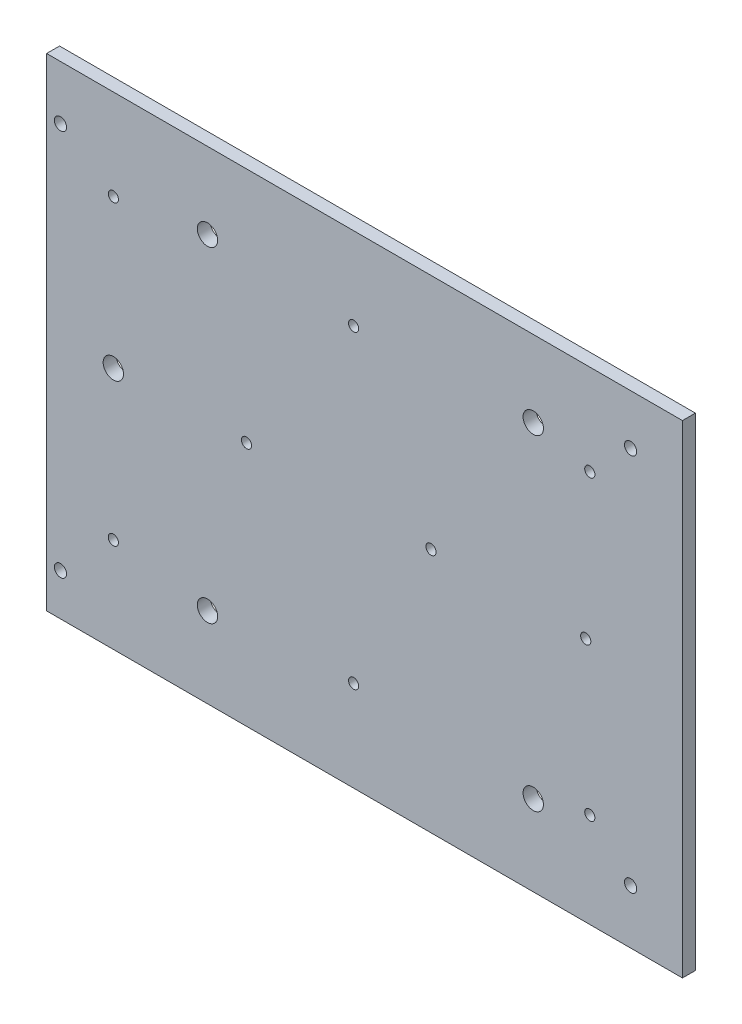
SolidWorks part; units mm, degrees
material "1060 Alloy"
ref_plane "Front Plane" through (0, 0, 0) normal (0, 0, 1) x (1, 0, 0)
ref_plane "Top Plane" through (0, 0, 0) normal (0, 1, 0) x (1, 0, 0)
ref_plane "Right Plane" through (0, 0, 0) normal (1, 0, 0) x (0, 0, -1)
sketch "Model" plane through (0, 0, 0) normal (0, 0, 1) x (1, 0, 0)
  line L0 (195.596, -46.5436) -> (195.6242, -46.5842)
  line L1 (195.6242, -46.5842) -> (195.667, -46.6123)
  line L2 (195.667, -46.6123) -> (195.7131, -46.6199)
  line L3 (195.7131, -46.6199) -> (223.0861, -46.6199)
  line L4 (223.0861, -46.6199) -> (223.0861, -165.0659)
  line L5 (223.0861, -165.0659) -> (66.9527, -165.0659)
  line L6 (66.9527, -165.0659) -> (66.9527, -46.5208)
  line L7 (66.9527, -46.5208) -> (195.5915, -46.5208)
  line L8 (195.5915, -46.5208) -> (195.596, -46.5436)
  spline S0 degree 3 poles (109.2626, -145.1929) (109.2626, -146.5998) (108.1198, -147.7426) (106.7129, -147.7426) (105.3062, -147.7426) (104.1635, -146.5998) (104.1635, -145.1929) knots 2 2 2 2 3 3 3 4 4 4 4
  spline S1 degree 3 poles (104.1635, -145.1929) (104.1635, -143.7862) (105.3062, -142.6435) (106.7129, -142.6435) (108.1198, -142.6435) (109.2626, -143.7862) (109.2626, -145.1929) knots 0 0 0 0 1 1 1 2 2 2 2
  spline S2 degree 3 poles (189.2129, -145.1929) (189.2129, -146.5723) (188.0926, -147.6933) (186.7132, -147.6933) (185.3334, -147.6933) (184.213, -146.5723) (184.213, -145.1929) knots 2 2 2 2 3 3 3 4 4 4 4
  spline S3 degree 3 poles (184.213, -145.1929) (184.213, -143.8134) (185.3334, -142.6931) (186.7132, -142.6931) (188.0926, -142.6931) (189.2129, -143.8134) (189.2129, -145.1929) knots 0 0 0 0 1 1 1 2 2 2 2
  spline S4 degree 3 poles (189.2129, -65.1924) (189.2129, -66.5716) (188.0926, -67.6942) (186.7132, -67.6942) (185.3334, -67.6942) (184.213, -66.5716) (184.213, -65.1924) knots 2 2 2 2 3 3 3 4 4 4 4
  spline S5 degree 3 poles (184.213, -65.1924) (184.213, -63.8132) (185.3334, -62.693) (186.7132, -62.693) (188.0926, -62.693) (189.2129, -63.8132) (189.2129, -65.1924) knots 0 0 0 0 1 1 1 2 2 2 2
  spline S6 degree 3 poles (109.213, -65.1924) (109.213, -66.5716) (108.0926, -67.6942) (106.7129, -67.6942) (105.3334, -67.6942) (104.2131, -66.5716) (104.2131, -65.1924) knots 2 2 2 2 3 3 3 4 4 4 4
  spline S7 degree 3 poles (104.2131, -65.1924) (104.2131, -63.8132) (105.3334, -62.693) (106.7129, -62.693) (108.0926, -62.693) (109.213, -63.8132) (109.213, -65.1924) knots 0 0 0 0 1 1 1 2 2 2 2
  spline S8 degree 3 poles (211.7669, -151.793) (211.7669, -152.6339) (211.0838, -153.3171) (210.2432, -153.3171) (209.4022, -153.3171) (208.719, -152.6339) (208.719, -151.793) knots 2 2 2 2 3 3 3 4 4 4 4
  spline S9 degree 3 poles (208.719, -151.793) (208.719, -150.9524) (209.4022, -150.2689) (210.2432, -150.2689) (211.0838, -150.2689) (211.7669, -150.9524) (211.7669, -151.793) knots 0 0 0 0 1 1 1 2 2 2 2
  spline S10 degree 3 poles (92.8348, -140.3787) (92.8348, -141.2195) (92.1517, -141.9028) (91.3111, -141.9028) (90.4701, -141.9028) (89.787, -141.2195) (89.787, -140.3787) knots 2 2 2 2 3 3 3 4 4 4 4
  spline S11 degree 3 poles (89.787, -140.3787) (89.787, -139.5355) (90.4701, -138.8548) (91.3111, -138.8548) (92.1517, -138.8548) (92.8348, -139.5355) (92.8348, -140.3787) knots 0 0 0 0 1 1 1 2 2 2 2
  spline S12 degree 3 poles (71.7672, -59.7924) (71.7672, -60.633) (71.084, -61.3163) (69.4021, -61.3163) (68.7193, -60.633) (68.7193, -59.7924) knots 2 2 2 2 3 3 4 4 4 4
  spline S13 degree 3 poles (68.7193, -59.7924) (68.7193, -58.9516) (69.4021, -58.2683) (71.084, -58.2683) (71.7672, -58.9516) (71.7672, -59.7924) knots 0 0 0 0 1 1 2 2 2 2
  spline S14 degree 3 poles (71.7672, -154.793) (71.7672, -155.6339) (71.084, -156.3171) (69.4021, -156.3171) (68.7193, -155.6339) (68.7193, -154.793) knots 2 2 2 2 3 3 4 4 4 4
  spline S15 degree 3 poles (68.7193, -154.793) (68.7193, -153.9524) (69.4021, -153.2689) (71.084, -153.2689) (71.7672, -153.9524) (71.7672, -154.793) knots 0 0 0 0 1 1 2 2 2 2
  spline S16 degree 3 poles (117.2132, -104.7934) (117.2132, -105.4945) (116.644, -106.0635) (115.943, -106.0635) (115.2422, -106.0635) (114.6731, -105.4945) (114.6731, -104.7934) knots 2 2 2 2 3 3 3 4 4 4 4
  spline S17 degree 3 poles (114.6731, -104.7934) (114.6731, -104.0925) (115.2422, -103.5234) (115.943, -103.5234) (116.644, -103.5234) (117.2132, -104.0925) (117.2132, -104.7934) knots 0 0 0 0 1 1 1 2 2 2 2
  spline S18 degree 3 poles (162.5131, -104.7934) (162.5131, -105.4945) (161.9436, -106.0635) (160.5421, -106.0635) (159.973, -105.4945) (159.973, -104.7934) knots 2 2 2 2 3 3 4 4 4 4
  spline S19 degree 3 poles (159.973, -104.7934) (159.973, -104.0925) (160.5421, -103.5234) (161.9436, -103.5234) (162.5131, -104.0925) (162.5131, -104.7934) knots 0 0 0 0 1 1 2 2 2 2
  spline S20 degree 3 poles (143.513, -66.7925) (143.513, -67.4936) (142.9439, -68.0625) (142.2428, -68.0625) (141.5421, -68.0625) (140.973, -67.4936) (140.973, -66.7925) knots 2 2 2 2 3 3 3 4 4 4 4
  spline S21 degree 3 poles (140.973, -66.7925) (140.973, -66.0916) (141.5421, -65.5226) (142.2428, -65.5226) (142.9439, -65.5226) (143.513, -66.0916) (143.513, -66.7925) knots 0 0 0 0 1 1 1 2 2 2 2
  spline S22 degree 3 poles (143.513, -142.793) (143.513, -143.4937) (142.9439, -144.0629) (142.2428, -144.0629) (141.5421, -144.0629) (140.973, -143.4937) (140.973, -142.793) knots 2 2 2 2 3 3 3 4 4 4 4
  spline S23 degree 3 poles (140.973, -142.793) (140.973, -142.0923) (141.5421, -141.5231) (142.2428, -141.5231) (142.9439, -141.5231) (143.513, -142.0923) (143.513, -142.793) knots 0 0 0 0 1 1 1 2 2 2 2
  spline S24 degree 3 poles (201.5129, -141.7929) (201.5129, -142.4936) (200.9438, -143.0631) (199.5423, -143.0631) (198.9732, -142.4936) (198.9732, -141.7929) knots 2 2 2 2 3 3 4 4 4 4
  spline S25 degree 3 poles (198.9732, -141.7929) (198.9732, -141.0922) (199.5423, -140.5227) (200.9438, -140.5227) (201.5129, -141.0922) (201.5129, -141.7929) knots 0 0 0 0 1 1 2 2 2 2
  spline S26 degree 3 poles (200.4033, -104.5826) (200.4033, -105.2837) (199.8338, -105.8526) (198.4323, -105.8526) (197.8632, -105.2837) (197.8632, -104.5826) knots 2 2 2 2 3 3 4 4 4 4
  spline S27 degree 3 poles (197.8632, -104.5826) (197.8632, -103.8817) (198.4323, -103.3127) (199.8338, -103.3127) (200.4033, -103.8817) (200.4033, -104.5826) knots 0 0 0 0 1 1 2 2 2 2
  spline S28 degree 3 poles (201.5129, -68.7941) (201.5129, -69.4926) (200.9438, -70.0641) (199.5423, -70.0641) (198.9732, -69.4926) (198.9732, -68.7941) knots 2 2 2 2 3 3 4 4 4 4
  spline S29 degree 3 poles (198.9732, -68.7941) (198.9732, -68.093) (199.5423, -67.524) (200.9438, -67.524) (201.5129, -68.093) (201.5129, -68.7941) knots 0 0 0 0 1 1 2 2 2 2
  spline S30 degree 3 poles (85.7429, -105.2938) (85.7429, -106.6731) (84.6226, -107.7932) (81.8637, -107.7932) (80.743, -106.6731) (80.743, -105.2938) knots 2 2 2 2 3 3 4 4 4 4
  spline S31 degree 3 poles (80.743, -105.2938) (80.743, -103.9146) (81.8637, -102.792) (84.6226, -102.792) (85.7429, -103.9146) (85.7429, -105.2938) knots 0 0 0 0 1 1 2 2 2 2
  spline S32 degree 3 poles (84.513, -141.7929) (84.513, -142.4936) (83.9439, -143.0631) (82.5424, -143.0631) (81.9733, -142.4936) (81.9733, -141.7929) knots 2 2 2 2 3 3 4 4 4 4
  spline S33 degree 3 poles (81.9733, -141.7929) (81.9733, -141.0922) (82.5424, -140.5227) (83.9439, -140.5227) (84.513, -141.0922) (84.513, -141.7929) knots 0 0 0 0 1 1 2 2 2 2
  spline S34 degree 3 poles (84.513, -68.7941) (84.513, -69.4926) (83.9439, -70.0641) (82.5424, -70.0641) (81.9733, -69.4926) (81.9733, -68.7941) knots 2 2 2 2 3 3 4 4 4 4
  spline S35 degree 3 poles (81.9733, -68.7941) (81.9733, -68.093) (82.5424, -67.524) (83.9439, -67.524) (84.513, -68.093) (84.513, -68.7941) knots 0 0 0 0 1 1 2 2 2 2
sketch "Sketch10" plane through (0, 0, 0) normal (0, 0, 1) x (1, 0, 0)
  line L1 (66.9527, -46.5208) -> (223.0861, -46.5208)
  line L2 (66.9527, -46.5208) -> (66.9527, -165.0659)
  line L3 (66.9527, -165.0659) -> (223.0861, -165.0659)
  line L4 (223.0861, -46.5208) -> (223.0861, -165.0659)
extrude "Boss-Extrude2" add sketch "Sketch10" along normal blind 3.175
sketch "Sketch11" plane through (0, 0, 3.175) normal (0, 0, 1) x (1, 0, 0)
  line L0 (66.9527, -46.5208) -> (195.5915, -46.5208) construction
  line L1 (106.4527, -65.2708) -> (186.4527, -65.2708) construction
  line L2 (106.4527, -65.2708) -> (106.4527, -145.2708) construction
  line L3 (106.4527, -145.2708) -> (186.4527, -145.2708) construction
  line L4 (186.4527, -65.2708) -> (186.4527, -145.2708) construction
  line L5 (66.9527, -165.0659) -> (66.9527, -46.5208) construction
  dimension "D1" = 80
  dimension "D2" = 80
  dimension "D3" = 18.75
  dimension "D4" = 39.5
hole_wizard "Ø5.0mm Dowel Hole1" positions "Sketch12" profile "Sketch13" hole size "Ø5.0" standard "ISO" end condition through all
sketch "Sketch12" plane through (0, 0, 3.175) normal (0, 0, 1) x (1, 0, 0)
  point P0 (106.4527, -65.2708)
  point P3 (186.4527, -65.2708)
  point P6 (186.4527, -145.2708)
  point P9 (106.4527, -145.2708)
sketch "Sketch13" plane through (106.4527, -65.2708, 3.175) normal (1, 0, 0) x (0, -1, 0)
  line L0 (0, 0) -> (0, 3.175)
  line L1 (0, 3.175) -> (2.5, 3.175)
  line L2 (2.5, 3.175) -> (2.5, 0)
  line L5 (2.5, 0) -> (0, 0)
  line L11 (0, -6.35) -> (0, 107.95) construction
  dimension "Thru Hole Dia." = 5
  dimension "Thru Hole Depth" = 3.175
sketch "Sketch14" plane through (0, 0, 3.175) normal (0, 0, 1) x (1, 0, 0)
  line L0 (66.9527, -165.0659) -> (66.9527, -46.5208) construction
  line L1 (66.9527, -46.5208) -> (195.5915, -46.5208) construction
  point P0 (70.3527, -59.7708)
  point P1 (210.3527, -58.7708)
  point P2 (210.3527, -151.7708)
  point P3 (70.3527, -154.7708)
  dimension "D1" = 3.4
  dimension "D2" = 13.25
  dimension "D3" = 95
  dimension "D4" = 140
  dimension "D5" = 93
  dimension "D6" = 3
hole_wizard "Ø3.0mm Dowel Hole1" positions "Sketch15" profile "Sketch16" hole size "Ø3.0" standard "ISO" end condition through all
sketch "Sketch15" plane through (0, 0, 0) normal (0, 0, -1) x (-1, 0, 0)
  point P0 (-210.3527, -58.7708)
  point P3 (-210.3527, -151.7708)
  point P6 (-70.3527, -154.7708)
  point P9 (-70.3527, -59.7708)
sketch "Sketch16" plane through (210.3527, -58.7708, 0) normal (1, 0, 0) x (0, 1, 0)
  line L0 (0, 0) -> (0, 3.175)
  line L1 (0, 3.175) -> (1.5, 3.175)
  line L2 (1.5, 3.175) -> (1.5, 0)
  line L5 (1.5, 0) -> (0, 0)
  line L11 (0, -6.35) -> (0, 107.95) construction
  dimension "Thru Hole Dia." = 3
  dimension "Thru Hole Depth" = 3.175
sketch "Sketch17" plane through (0, 0, 0) normal (0, 0, -1) x (-1, 0, 0)
  line L0 (-66.9527, -46.5208) -> (-195.5915, -46.5208) construction
  line L1 (-200.3361, -68.7708) -> (-83.3361, -68.7708) construction
  line L2 (-200.3361, -68.7708) -> (-200.3361, -141.7708) construction
  line L3 (-200.3361, -141.7708) -> (-83.3361, -141.7708) construction
  line L4 (-83.3361, -68.7708) -> (-83.3361, -141.7708) construction
  line L5 (-223.0861, -46.6199) -> (-223.0861, -165.0659) construction
  dimension "D1" = 117
  dimension "D2" = 73
  dimension "D3" = 22.25
  dimension "D4" = 22.75
hole_wizard "Ø2.5mm Dowel Hole1" positions "Sketch18" profile "Sketch19" hole size "Ø2.5" standard "ISO" end condition through all
sketch "Sketch18" plane through (0, 0, 0) normal (0, 0, -1) x (-1, 0, 0)
  point P0 (-200.3361, -68.7708)
  point P3 (-83.3361, -68.7708)
  point P6 (-83.3361, -141.7708)
  point P9 (-200.3361, -141.7708)
sketch "Sketch19" plane through (200.3361, -68.7708, 0) normal (1, 0, 0) x (0, 1, 0)
  line L0 (0, 0) -> (0, 3.175)
  line L1 (0, 3.175) -> (1.25, 3.175)
  line L2 (1.25, 3.175) -> (1.25, 0)
  line L5 (1.25, 0) -> (0, 0)
  line L11 (0, -6.35) -> (0, 107.95) construction
  dimension "Thru Hole Dia." = 2.5
  dimension "Thru Hole Depth" = 3.175
sketch "Sketch20" plane through (0, 0, 0) normal (0, 0, -1) x (-1, 0, 0)
  line L0 (-83.3361, -68.7708) -> (-83.3361, -141.7708) construction
  line L1 (-223.0861, -46.6199) -> (-223.0861, -165.0659) construction
  point P0 (-199.3361, -104.7708)
  point P1 (-161.3361, -104.7708)
  point P2 (-116.0361, -104.7708)
  point P3 (-142.3361, -66.7708)
  point P4 (-142.3361, -142.7708)
  point P5 (-91.3361, -140.2708)
  point P6 (-83.3361, -105.2708)
  dimension "D1" = 38
  dimension "D2" = 45.3
  dimension "D3" = 38
  dimension "D4" = 0.5
  dimension "D5" = 23.75
  dimension "D6" = 38
  dimension "D7" = 19
  dimension "D8" = 19
  dimension "D9" = 51
  dimension "D10" = 35
hole_wizard "Ø2.5mm Dowel Hole2" positions "Sketch21" profile "Sketch22" hole size "Ø2.5" standard "ISO" end condition through all
sketch "Sketch21" plane through (0, 0, 0) normal (0, 0, -1) x (-1, 0, 0)
  point P0 (-199.3361, -104.7708)
  point P3 (-161.3361, -104.7708)
  point P6 (-116.0361, -104.7708)
  point P9 (-142.3361, -66.7708)
  point P12 (-142.3361, -142.7708)
sketch "Sketch22" plane through (199.3361, -104.7708, 0) normal (1, 0, 0) x (0, 1, 0)
  line L0 (0, 0) -> (0, 3.175)
  line L1 (0, 3.175) -> (1.25, 3.175)
  line L2 (1.25, 3.175) -> (1.25, 0)
  line L5 (1.25, 0) -> (0, 0)
  line L11 (0, -6.35) -> (0, 107.95) construction
  dimension "Thru Hole Dia." = 2.5
  dimension "Thru Hole Depth" = 3.175
hole_wizard "Ø5.0mm Dowel Hole2" positions "Sketch23" profile "Sketch24" hole size "Ø5.0" standard "ISO" end condition through all
sketch "Sketch23" plane through (0, 0, 0) normal (0, 0, -1) x (-1, 0, 0)
  point P0 (-83.3361, -105.2708)
sketch "Sketch24" plane through (83.3361, -105.2708, 0) normal (1, 0, 0) x (0, 1, 0)
  line L0 (0, 0) -> (0, 3.175)
  line L1 (0, 3.175) -> (2.5, 3.175)
  line L2 (2.5, 3.175) -> (2.5, 0)
  line L5 (2.5, 0) -> (0, 0)
  line L11 (0, -6.35) -> (0, 107.95) construction
  dimension "Thru Hole Dia." = 5
  dimension "Thru Hole Depth" = 3.175
